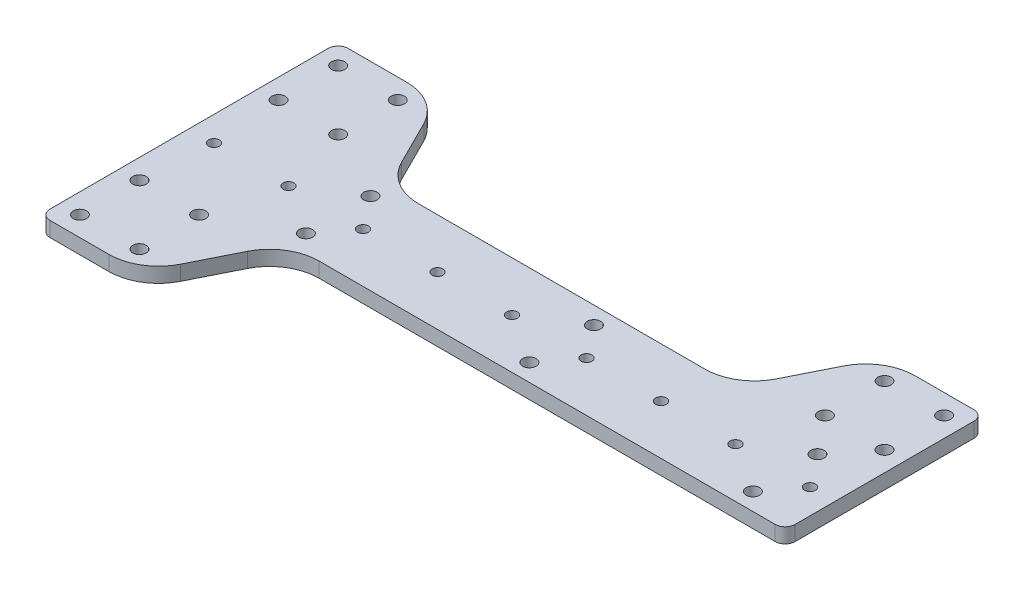
SolidWorks part; units mm, degrees
material "碳纤维"
ref_plane "前视基准面" through (0, 0, 0) normal (0, 0, 1) x (1, 0, 0)
ref_plane "上视基准面" through (0, 0, 0) normal (0, 1, 0) x (1, 0, 0)
ref_plane "右视基准面" through (0, 0, 0) normal (1, 0, 0) x (0, 0, -1)
sketch "草图1" plane through (0, 0, 0) normal (0, 1, 0) x (1, 0, 0)
  line L0 (10, 10) -> (10, 30)
  line L1 (-10, -30) -> (10, -30)
  line L2 (-10, -30) -> (-10, 30)
  line L3 (-10, 30) -> (10, 30)
  line L4 (10, -30) -> (10, -10)
  line L5 (0, 30) -> (0, -30) construction
  line L6 (-10, 0) -> (10, 0) construction
  line L11 (10, 10) -> (100, 10)
  line L13 (10, -10) -> (120, -10)
  line L14 (120, 10) -> (120, -10)
  line L15 (65, -10) -> (65, 10) construction
  line L16 (10, 0) -> (120, 0) construction
  line L17 (120, 30) -> (100, 30)
  line L22 (100, 10) -> (100, 30)
  line L24 (120, 10) -> (120, 30)
  point P0 (0, 0)
  point P86 (65, 0)
  dimension "D1" = 110
  dimension "D2" = 20
  dimension "D3" = 60
extrude "凸台-拉伸1" add sketch "草图1" along normal blind 3
sketch "草图2" plane through (0, 3, 0) normal (0, 1, 0) x (1, 0, 0)
  line L0 (0, 30) -> (0, 0) construction
  line L1 (10, 30) -> (-10, 30) construction
  line L2 (10, 20) -> (-10, 20) construction
  line L3 (55, 10) -> (55, 33.2848) construction
  line L4 (-10, 30) -> (-10, -30) construction
  line L5 (0, 0) -> (120, 0) construction
  line L6 (120, -10) -> (120, 30) construction
  line L7 (65, 10) -> (65, -10) construction
  line L8 (100, 10) -> (10, 10) construction
  line L9 (10, -10) -> (120, -10) construction
  line L10 (100, 10) -> (10, 10) construction
  line L11 (120, -10) -> (120, 30) construction
  line L12 (100, 10) -> (10, 10) construction
  circle A0 centre (-6, 26) radius 1.35
  circle A1 centre (-6, 14) radius 1.35
  circle A2 centre (6, 14) radius 1.35
  circle A3 centre (6, 26) radius 1.35
  circle A4 centre (6, -26) radius 1.35
  circle A5 centre (6, -14) radius 1.35
  circle A6 centre (-6, -14) radius 1.35
  circle A7 centre (-6, -26) radius 1.35
  circle A8 centre (110, 6.5) radius 1.35
  circle A10 centre (20, 6.5) radius 1.35
  circle A11 centre (65, 6.5) radius 1.35
  circle A12 centre (65, -6.5) radius 1.35
  circle A13 centre (20, -6.5) radius 1.35
  circle A14 centre (110, -6.5) radius 1.35
  circle A15 centre (104, 26) radius 1.35
  circle A16 centre (104, 14) radius 1.35
  circle A17 centre (116, 14) radius 1.35
  circle A18 centre (116, 26) radius 1.35
  dimension "D3" = 2.7
  dimension "D4" = 10
  dimension "D1" = 12
  dimension "D2" = 12
  dimension "D5" = 3.5
  dimension "D6" = 10
extrude "切除-拉伸1" cut sketch "草图2" against normal through all
sketch "草图3" plane through (0, 3, 0) normal (0, 1, 0) x (1, 0, 0)
  line L0 (120, -10) -> (120, 30) construction
  line L1 (0, 0) -> (115, 0) construction
  circle A14 centre (115, 0) radius 1.1
  circle A15 centre (100, 0) radius 1.1
  circle A16 centre (85, 0) radius 1.1
  circle A17 centre (70, 0) radius 1.1
  circle A18 centre (55, 0) radius 1.1
  circle A19 centre (40, 0) radius 1.1
  circle A20 centre (25, 0) radius 1.1
  circle A21 centre (10, 0) radius 1.1
  circle A22 centre (-5, 0) radius 1.1
  dimension "D3" = 15
  dimension "D1" = 5
  dimension "D2" = 2.2
extrude "切除-拉伸2" cut sketch "草图3" against normal through all
sketch "草图4" plane through (0, 3, 0) normal (0, 1, 0) x (1, 0, 0)
  line L1 (55, 10) -> (55, -10) construction
  line L6 (10, -30) -> (20, -10)
  line L7 (10, -10) -> (120, -10) construction
  line L8 (10, -30) -> (10, -10) construction
  line L9 (20, -10) -> (10, -10)
  line L10 (10, -10) -> (10, -30)
  line L11 (0, 0) -> (31.2351, 0) construction
  line L12 (20, 10) -> (10, 10)
  line L13 (10, 30) -> (20, 10)
  line L14 (10, 10) -> (10, 30)
  line L15 (100, 30) -> (90, 10)
  line L16 (100, 10) -> (100, 30)
  line L17 (90, 10) -> (100, 10)
  line L21 (100, 10) -> (10, 10) construction
  dimension "D3" = 10
extrude "凸台-拉伸2" add sketch "草图4" against normal up to surface (3 mm away) up to face at (115, 0, 1.1)
fillet "圆角1" radius 10 6 edges at (10, 1.5, -30) (20, 1.5, -10) (10, 1.5, 30) (20, 1.5, 10) (100, 1.5, -30) (90, 1.5, -10)
fillet "圆角2" radius 2 4 edges at (120, 1.5, 10) (-10, 1.5, 30) (-10, 1.5, -30) (120, 1.5, -30)
